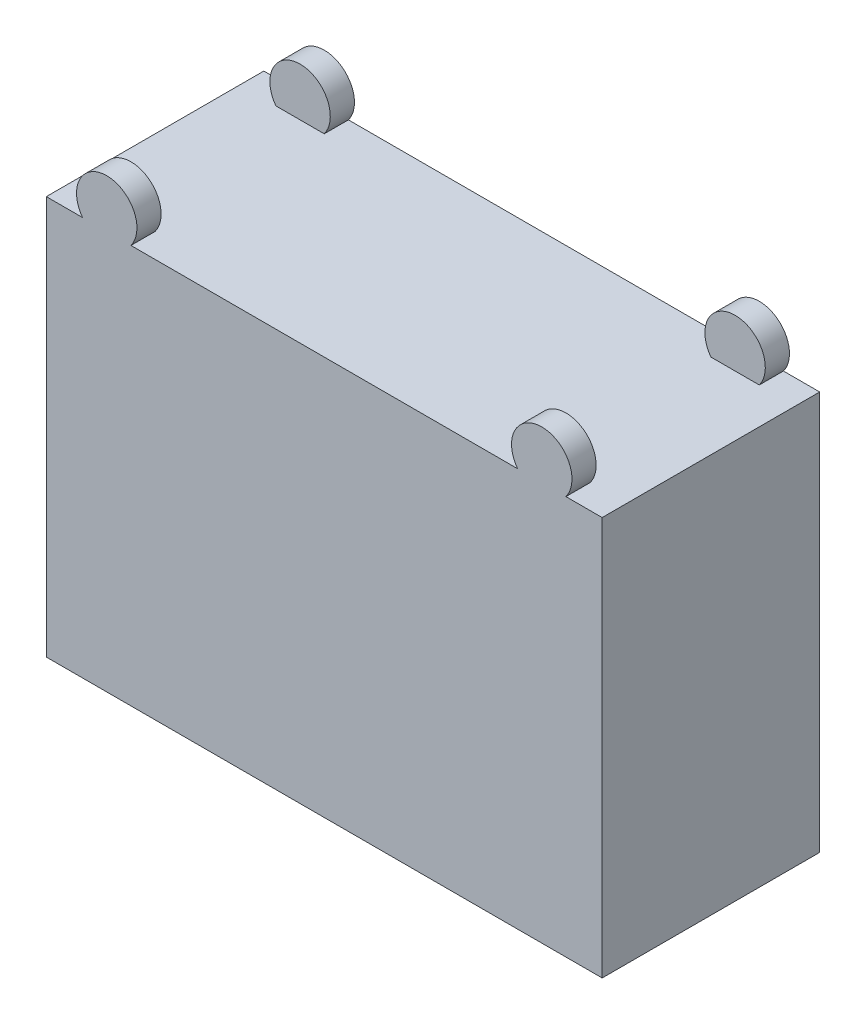
SolidWorks part; units mm, degrees
material "Maple"
ref_plane "Front" through (0, 0, 0) normal (0, 0, 1) x (1, 0, 0)
ref_plane "Top" through (0, 0, 0) normal (0, 1, 0) x (1, 0, 0)
ref_plane "Right" through (0, 0, 0) normal (1, 0, 0) x (0, 0, -1)
sketch "Sketch1" plane through (0, 0, 0) normal (0, 1, 0) x (1, 0, 0)
  line L0 (-584.2, 228.6) -> (584.2, -228.6) construction
  line L1 (-584.2, 228.6) -> (584.2, 228.6)
  line L2 (-584.2, 228.6) -> (-584.2, -228.6)
  line L3 (-584.2, -228.6) -> (584.2, -228.6)
  line L4 (584.2, 228.6) -> (584.2, -228.6)
  dimension "D1" = 1168.4
  dimension "D2" = 457.2
extrude "Boss-Extrude1" add sketch "Sketch1" along normal blind 838.2
sketch "Sketch2" plane through (0, 0, 228.6) normal (0, 0, 1) x (1, 0, 0)
  line L0 (-457.2, 876.3) -> (457.2, 876.3) construction
  line L1 (0, 876.3) -> (0, 838.2) construction
  line L2 (-584.2, 838.2) -> (584.2, 838.2) construction
  circle A0 centre (-457.2, 876.3) radius 63.5
  circle A1 centre (457.2, 876.3) radius 63.5
  dimension "D1" = 127
  dimension "D2" = 38.1
  dimension "D3" = 914.4
extrude "Boss-Extrude2" add sketch "Sketch2" against normal blind 50.8
mirror "Mirror1" about plane through (0, 0, 0) normal (0, 0, 1) of "Boss-Extrude2"
